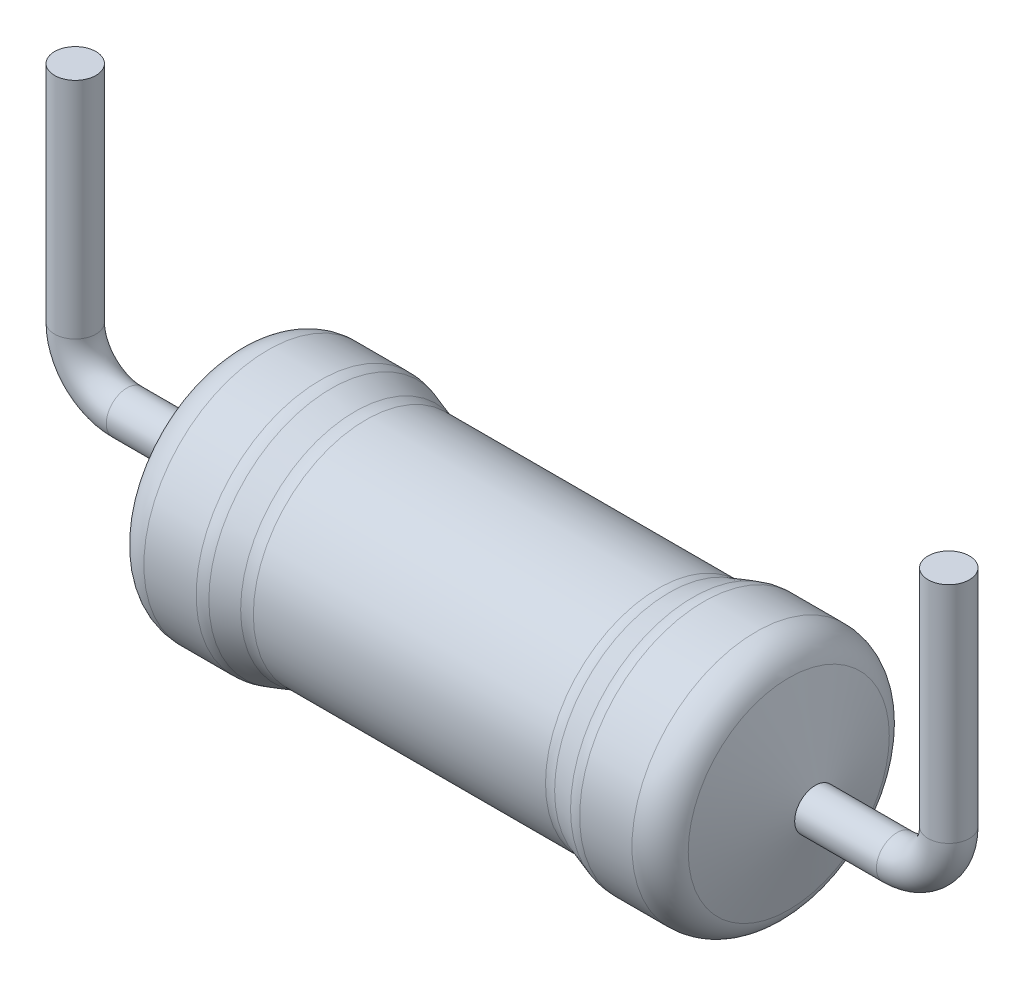
SolidWorks part; units mm, degrees
ref_plane "Front Plane" through (0, 0, 0) normal (0, 0, 1) x (1, 0, 0)
ref_plane "Top Plane" through (0, 0, 0) normal (0, 1, 0) x (1, 0, 0)
ref_plane "Right Plane" through (0, 0, 0) normal (1, 0, 0) x (0, 0, -1)
sketch "Sketch1" plane through (0, 0, 0) normal (0, 0, 1) x (1, 0, 0)
  line L0 (0, 0) -> (4.4, 0)
  line L1 (4.4, 0) -> (4.4, 0.3)
  line L2 (4.4, 0.3) -> (3.9, 1.8)
  line L3 (3.9, 1.8) -> (2.7, 1.8)
  line L4 (2.7, 1.8) -> (2.2, 1.6333)
  line L5 (2.2, 1.6333) -> (-2.2, 1.6333)
  line L6 (-2.2, 1.6333) -> (-2.7, 1.8)
  line L7 (-2.7, 1.8) -> (-3.9, 1.8)
  line L8 (-3.9, 1.8) -> (-4.4, 0.3)
  line L9 (-4.4, 0.3) -> (-4.4, 0)
  line L10 (-4.4, 0) -> (0, 0)
  point P2 (3.3, 1.8)
  dimension "D1" = 0.3
  dimension "D2" = 0.3
  dimension "D3" = 4.4
  dimension "D4" = 4.4
  dimension "D5" = 1.8
  dimension "D6" = 1.8
  dimension "D7" = 0.5
  dimension "D8" = 0.5
  dimension "D9" = 1.2
  dimension "D12" = 0.5
  dimension "D13" = 1.6333
revolve "Revolve1" add sketch "Sketch1" angle 360 about L0
fillet "Fillet1" radius 0.5 6 edges at (-3.9, 0, 1.8) (-2.7, 0, 1.8) (-2.2, 0, 1.6333) (2.2, 0, 1.6333) (2.7, 0, 1.8) (3.9, 0, 1.8)
sketch "Sketch4" plane through (4.4, 0, 0) normal (1, 0, 0) x (0, 0, -1)
  circle A0 centre (0, 0) radius 0.3
  circle A1 centre (0, 0) radius 0.3 construction
sketch "Sketch6" plane through (0, 0, 0) normal (0, 0, 1) x (1, 0, 0)
  line L0 (4.4, 0) -> (5.585, 0)
  line L1 (6.335, 0.75) -> (6.335, 4)
  line L2 (4.4, 0) -> (-5.585, 0)
  line L3 (-6.335, 0.75) -> (-6.335, 4)
  arc A0 (-5.585, 0) -> (-6.335, 0.75) centre (-5.585, 0.75) cw
  arc A1 (5.585, 0) -> (6.335, 0.75) centre (5.585, 0.75) ccw
  point P8 (-6.335, 0)
  point P11 (6.335, 0)
  dimension "D5" = 0.75
  dimension "D1" = 1.935
  dimension "D2" = 4
  dimension "D3" = 10.735
  dimension "D4" = 4
sweep "Sweep1" add profiles "Sketch4" path "Sketch6"
